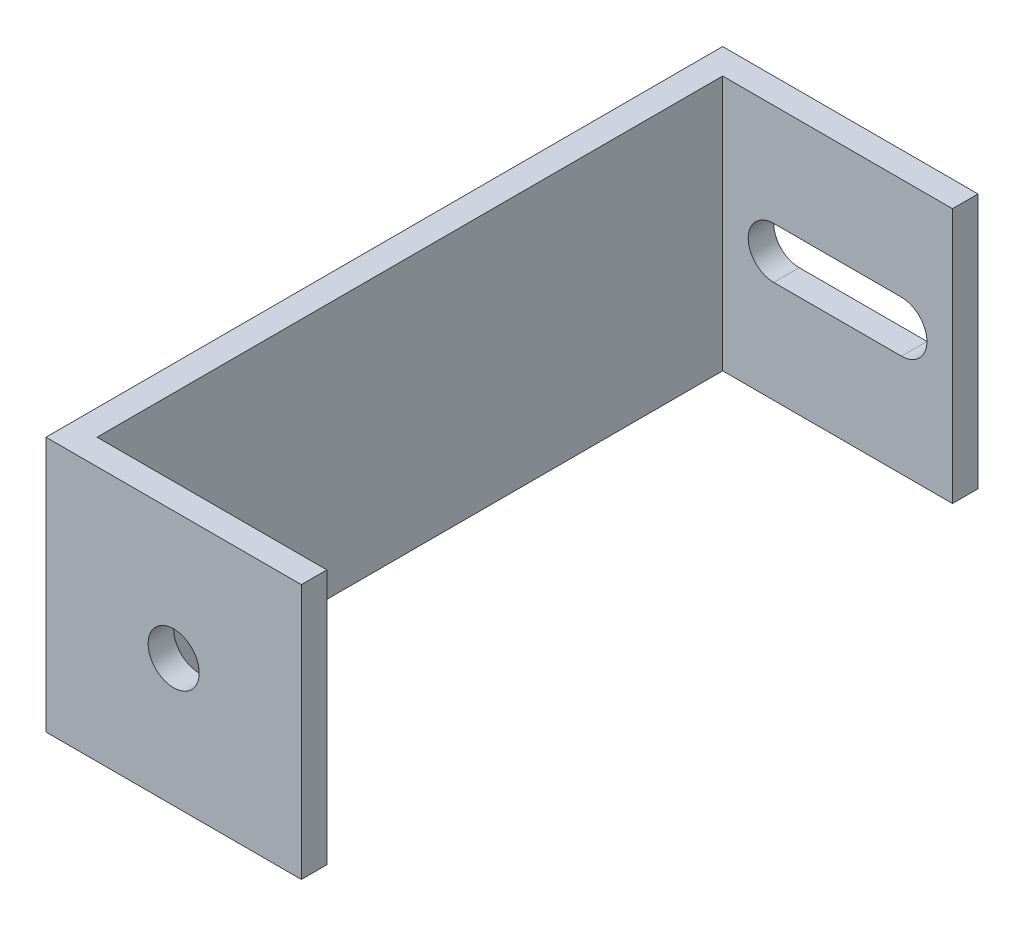
SolidWorks part; units mm, degrees
ref_plane "Front Plane" through (0, 0, 0) normal (0, 0, 1) x (1, 0, 0)
ref_plane "Top Plane" through (0, 0, 0) normal (0, 1, 0) x (1, 0, 0)
ref_plane "Right Plane" through (0, 0, 0) normal (1, 0, 0) x (0, 0, -1)
sketch "Sketch1" plane through (0, 0, 0) normal (0, 0, 1) x (1, 0, 0)
  line L1 (-10, 10) -> (10, 10)
  line L2 (-10, 10) -> (-10, -10)
  line L3 (-10, -10) -> (10, -10)
  line L4 (10, 10) -> (10, -10)
  line L5 (-10, 10) -> (10, -10) construction
  line L6 (-10, -10) -> (10, 10) construction
  point P0 (0, 0)
  dimension "D1" = 20
  dimension "D2" = 20
extrude "Boss-Extrude1" add sketch "Sketch1" along normal blind 2
sketch "Sketch2" plane through (0, 0, 2) normal (0, 0, 1) x (1, 0, 0)
  line L0 (-10, -10) -> (10, -10) construction
  line L1 (-10, 10) -> (-8, 10)
  line L2 (-10, 10) -> (-10, -10)
  line L3 (-10, -10) -> (-8, -10)
  line L4 (-8, 10) -> (-8, -10)
  dimension "D1" = 2
extrude "Boss-Extrude2" add sketch "Sketch2" along normal blind 51
sketch "Sketch3" plane through (-8, 0, 0) normal (1, 0, 0) x (0, 0, -1)
  line L0 (-53, -10) -> (-2, -10) construction
  line L1 (-53, 10) -> (-51, 10)
  line L2 (-53, 10) -> (-53, -10)
  line L3 (-53, -10) -> (-51, -10)
  line L4 (-51, 10) -> (-51, -10)
  dimension "D1" = 2
extrude "Boss-Extrude3" add sketch "Sketch3" along normal blind 18
sketch "Sketch4" plane through (0, 0, 53) normal (0, 0, 1) x (1, 0, 0)
  line L0 (10, 10) -> (10, -10) construction
  line L1 (10, 10) -> (-10, 10) construction
  circle A0 centre (0, 0) radius 2
  dimension "D1" = 4
  dimension "D2" = 10
  dimension "D3" = 10
extrude "Cut-Extrude1" cut sketch "Sketch4" against normal blind 18
sketch "Sketch5" plane through (0, 0, 0) normal (0, 0, -1) x (-1, 0, 0)
  line L0 (-6, 0) -> (4, 0) construction
  line L1 (-6, 2) -> (4, 2)
  line L2 (-6, -2) -> (4, -2)
  line L3 (10, -10) -> (-10, -10) construction
  line L4 (-10, -10) -> (-10, 10) construction
  arc A0 (-6, 2) -> (-6, -2) centre (-6, 0) ccw
  arc A1 (4, -2) -> (4, 2) centre (4, 0) ccw
  point P2 (-1, 0)
  dimension "D1" = 2
  dimension "D2" = 10
  dimension "D3" = 10
  dimension "D4" = 4
extrude "Cut-Extrude2" cut sketch "Sketch5" against normal blind 18
